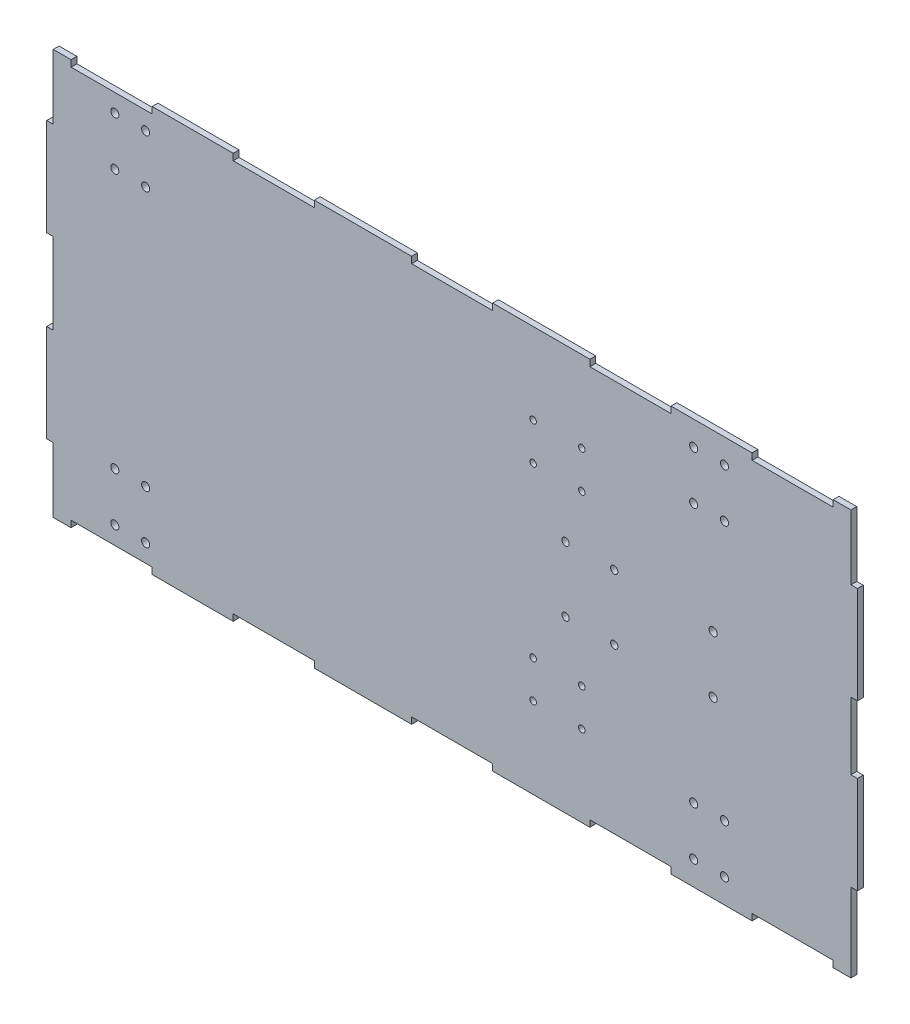
SolidWorks part; units mm, degrees
material "处理板，复杂型"
ref_plane "前视基准面" through (0, 0, 0) normal (0, 0, 1) x (1, 0, 0)
ref_plane "上视基准面" through (0, 0, 0) normal (0, 1, 0) x (1, 0, 0)
ref_plane "右视基准面" through (0, 0, 0) normal (1, 0, 0) x (0, 0, -1)
sketch "草图1" plane through (0, 0, 0) normal (0, 0, 1) x (1, 0, 0)
  line L0 (-28.0519, 0) -> (53.0983, 0) construction
  line L1 (-250, 125) -> (250, 125)
  line L2 (-250, 125) -> (-250, -125)
  line L3 (-250, -125) -> (250, -125)
  line L4 (250, 125) -> (250, -125)
  line L5 (0, 24.8794) -> (0, -28.6642) construction
  dimension "D1" = 500
  dimension "D2" = 250
  dimension "D3" = 250
  dimension "D4" = 125
extrude "凸台-拉伸1" add sketch "草图1" along normal blind 3.6
sketch "草图2" plane through (0, 0, 3.6) normal (0, 0, 1) x (1, 0, 0)
  line L0 (-311.6494, 0) -> (312.6882, 0) construction
  line L1 (0, 183.6134) -> (0, -234.2606) construction
  line L2 (-323.1181, 121) -> (406.0517, 121) construction
  line L3 (296.1915, -121) -> (-344.6593, -121) construction
  line L4 (250, 125) -> (-250, 125) construction
  line L5 (-250, -125) -> (250, -125) construction
  line L6 (0, -183.6134) -> (0, 234.2606) construction
  line L7 (-25, 125) -> (25, 125)
  line L8 (-25, 125) -> (-25, 121)
  line L9 (-25, 121) -> (25, 121)
  line L10 (25, 125) -> (25, 121)
  line L11 (-135, 125) -> (-85, 125)
  line L12 (-135, 125) -> (-135, 121)
  line L13 (-135, 121) -> (-85, 121)
  line L14 (-85, 125) -> (-85, 121)
  line L15 (-235, 125) -> (-185, 125)
  line L16 (-235, 125) -> (-235, 121)
  line L17 (-235, 121) -> (-185, 121)
  line L18 (-185, 125) -> (-185, 121)
  line L19 (85, 125) -> (135, 125)
  line L20 (85, 125) -> (85, 121)
  line L21 (85, 121) -> (135, 121)
  line L22 (135, 125) -> (135, 121)
  line L23 (185, 125) -> (235, 125)
  line L24 (185, 125) -> (185, 121)
  line L25 (185, 121) -> (235, 121)
  line L26 (235, 125) -> (235, 121)
  line L27 (235, -125) -> (235, -121)
  line L28 (185, -121) -> (235, -121)
  line L29 (185, -125) -> (185, -121)
  line L30 (185, -125) -> (235, -125)
  line L31 (135, -125) -> (135, -121)
  line L32 (85, -121) -> (135, -121)
  line L33 (85, -125) -> (85, -121)
  line L34 (85, -125) -> (135, -125)
  line L35 (-185, -125) -> (-185, -121)
  line L36 (-235, -121) -> (-185, -121)
  line L37 (-235, -125) -> (-235, -121)
  line L38 (-235, -125) -> (-185, -125)
  line L39 (-85, -125) -> (-85, -121)
  line L40 (-135, -121) -> (-85, -121)
  line L41 (-135, -125) -> (-135, -121)
  line L42 (-135, -125) -> (-85, -125)
  line L43 (25, -125) -> (25, -121)
  line L44 (-25, -121) -> (25, -121)
  line L45 (-25, -125) -> (-25, -121)
  line L46 (-25, -125) -> (25, -125)
  line L47 (-323.1181, -121) -> (406.0517, -121) construction
  dimension "D1" = 4
  dimension "D2" = 4
  dimension "D3" = 50
  dimension "D4" = 25
  dimension "D5" = 50
  dimension "D6" = 60
  dimension "D7" = 50
  dimension "D8" = 50
  dimension "D9" = 60
  dimension "D10" = 50
  dimension "D11" = 50
  dimension "D12" = 50
extrude "切除-拉伸1" cut sketch "草图2" against normal blind 3.6
sketch "草图3" plane through (0, 0, 3.6) normal (0, 0, 1) x (1, 0, 0)
  line L0 (-246, 195.56) -> (-246, -183.094) construction
  line L1 (246, 211.6619) -> (246, -187.2493) construction
  line L2 (250, -125) -> (250, 125) construction
  line L3 (-250, 125) -> (-250, -125) construction
  line L4 (-276.8358, 0) -> (321.3039, 0) construction
  line L5 (0, 237.0518) -> (0, -225.1956) construction
  line L7 (-250, 25) -> (-246, 25)
  line L8 (-250, 25) -> (-250, -25)
  line L9 (-250, -25) -> (-246, -25)
  line L10 (-246, 25) -> (-246, -25)
  line L11 (-250, 135) -> (-246, 135)
  line L12 (-250, 135) -> (-250, 85)
  line L13 (-250, 85) -> (-246, 85)
  line L14 (-246, 135) -> (-246, 85)
  line L19 (-250, -85) -> (-246, -85)
  line L20 (-250, -85) -> (-250, -135)
  line L21 (-250, -135) -> (-246, -135)
  line L22 (-246, -85) -> (-246, -135)
  line L27 (246, 25) -> (250, 25)
  line L28 (246, 25) -> (246, -16.4485)
  line L29 (246, -16.4485) -> (250, -16.4485)
  line L30 (250, 25) -> (250, -16.4485)
  line L31 (246, -76.4485) -> (250, -76.4485)
  line L32 (246, -76.4485) -> (246, -126.4485)
  line L33 (246, -126.4485) -> (250, -126.4485)
  line L34 (250, -76.4485) -> (250, -126.4485)
  line L39 (246, 135) -> (250, 135)
  line L40 (246, 135) -> (246, 85)
  line L41 (246, 85) -> (250, 85)
  line L42 (250, 135) -> (250, 85)
  dimension "D1" = 4
  dimension "D2" = 4
  dimension "D3" = 41.4485
  dimension "D4" = 25
  dimension "D5" = 50
  dimension "D6" = 60
  dimension "D7" = 50
  dimension "D8" = 60
  dimension "D9" = 50
  dimension "D10" = 25
  dimension "D11" = 50
  dimension "D12" = 60
  dimension "D13" = 60
  dimension "D14" = 50
extrude "切除-拉伸2" cut sketch "草图3" against normal blind 3.6
sketch "草图4" plane through (0, 0, 3.6) normal (0, 0, 1) x (1, 0, 0)
  line L0 (80, 177.8998) -> (80, -175.3028) construction
  line L1 (250, 25) -> (250, 85) construction
  line L2 (25, -125) -> (85, -125) construction
  line L3 (85, 125) -> (25, 125) construction
  circle A0 centre (80, 75) radius 2
  circle A1 centre (80, -52) radius 2
  circle A2 centre (80, 52) radius 2
  circle A3 centre (80, -75) radius 2
  dimension "D2" = 4
  dimension "D3" = 4
  dimension "D4" = 4
  dimension "D5" = 4
  dimension "D1" = 170
  dimension "D6" = 23
  dimension "D7" = 23
  dimension "D8" = 50
  dimension "D9" = 50
extrude "切除-拉伸3" cut sketch "草图4" against normal through all
sketch "草图5" plane through (0, 0, 3.6) normal (0, 0, 1) x (1, 0, 0)
  line L1 (80, 77) -> (80, -192.2746) construction
  line L2 (65, 157.0459) -> (65, -178.7667) construction
  circle A0 centre (80, 75) radius 2 construction
  circle A1 centre (50, 75) radius 2
  circle A2 centre (50, 52) radius 2
  circle A3 centre (50, -52) radius 2
  circle A4 centre (50, -75) radius 2
  circle A5 centre (80, -75) radius 2 construction
  point P18 (78, -75)
  point P19 (78, 75)
  dimension "D2" = 4
  dimension "D3" = 4
  dimension "D4" = 4
  dimension "D5" = 4
  dimension "D1" = 15
  dimension "D6" = 15
  dimension "D7" = 23
  dimension "D8" = 23
extrude "切除-拉伸4" cut sketch "草图5" against normal blind 10
sketch "草图6" plane through (0, 0, 3.6) normal (0, 0, 1) x (1, 0, 0)
  line L0 (-339.6978, 0) -> (346.5541, 0) construction
  line L1 (166, 278.0326) -> (166, -308.1608) construction
  line L2 (246, -76.4485) -> (246, -125) construction
  circle A0 centre (166, -42.0819) radius 2
  circle A1 centre (166, 43.4537) radius 2
  dimension "D2" = 4
  dimension "D3" = 4
  dimension "D1" = 80
sketch "草图7" plane through (0, 0, 3.6) normal (0, 0, 1) x (1, 0, 0)
  line L0 (-334.4545, 0) -> (340.193, 0) construction
  line L1 (161, 281.5485) -> (161, -235.7283) construction
  line L3 (246, 125) -> (246, 85) construction
  circle A0 centre (161, -17.5) radius 2.5
  circle A1 centre (161, 17.5) radius 2.5
  dimension "D2" = 5
  dimension "D3" = 5
  dimension "D4" = 17.5
  dimension "D1" = 17.5
  dimension "D5" = 85
extrude "切除-拉伸5" cut sketch "草图7" against normal blind 10
sketch "草图8" plane through (0, 0, 3.6) normal (0, 0, 1) x (1, 0, 0)
  line L0 (-388.5194, 0) -> (343.938, 0) construction
sketch "草图9" plane through (0, 0, 3.6) normal (0, 0, 1) x (1, 0, 0)
  line L0 (-358.9403, 0) -> (360.3982, 0) construction
  line L1 (-192.5941, 20) -> (334.2702, 20) construction
  line L2 (-192.5941, -20) -> (334.2702, -20) construction
  line L3 (100, 32.9954) -> (100, -35.9626) construction
  line L4 (70, 32.9954) -> (70, -30.7583) construction
  circle A0 centre (70, 20) radius 2.25
  circle A1 centre (100, 20) radius 2.25
  circle A2 centre (70, -20) radius 2.25
  circle A3 centre (100, -20) radius 2.25
  dimension "D5" = 4.5
  dimension "D6" = 4.5
  dimension "D7" = 4.5
  dimension "D8" = 4.5
  dimension "D1" = 20
  dimension "D2" = 20
  dimension "D3" = 100
  dimension "D4" = 30
extrude "切除-拉伸6" cut sketch "草图9" against normal through all
sketch "草图10" plane through (0, 0, 3.6) normal (0, 0, 1) x (1, 0, 0)
  line L0 (-409.9615, 0) -> (661.7165, 0) construction
  line L1 (140, 288.4622) -> (140, -301.2212) construction
  line L2 (110, 30) -> (110, -30) construction
  line L3 (-180, 346.961) -> (-180, -356.6399) construction
  line L4 (149, 303.3704) -> (149, -316.9245) construction
  line L5 (168, 303.3704) -> (168, -301.2212) construction
  line L6 (-189, 335.1326) -> (-189, -301.2212) construction
  line L7 (-208, 382.9709) -> (-208, -301.2212) construction
  circle A0 centre (-208, 110) radius 2.5
  circle A1 centre (-189, 110) radius 2.5
  circle A2 centre (-208, 80) radius 2.5
  circle A3 centre (-189, 80) radius 2.5
  circle A4 centre (-189, -110) radius 2.5
  circle A5 centre (-189, -80) radius 2.5
  circle A6 centre (-208, -80) radius 2.5
  circle A7 centre (-208, -110) radius 2.5
  circle A8 centre (149, 110) radius 2.5
  circle A9 centre (168, 110) radius 2.5
  circle A10 centre (149, 80) radius 2.5
  circle A11 centre (168, 80) radius 2.5
  circle A12 centre (168, -110) radius 2.5
  circle A13 centre (168, -80) radius 2.5
  circle A14 centre (149, -80) radius 2.5
  circle A15 centre (149, -110) radius 2.5
  dimension "D8" = 5
  dimension "D9" = 5
  dimension "D10" = 5
  dimension "D11" = 5
  dimension "D15" = 5
  dimension "D16" = 5
  dimension "D17" = 5
  dimension "D18" = 5
  dimension "D1" = 589.6834
  dimension "D2" = 30
  dimension "D3" = 320
  dimension "D4" = 9
  dimension "D5" = 19
  dimension "D6" = 9
  dimension "D7" = 19
  dimension "D12" = 30
  dimension "D13" = 30
  dimension "D14" = 80
  dimension "D19" = 30
  dimension "D20" = 30
  dimension "D21" = 80
  dimension "D22" = 80
extrude "切除-拉伸7" cut sketch "草图10" against normal through all
